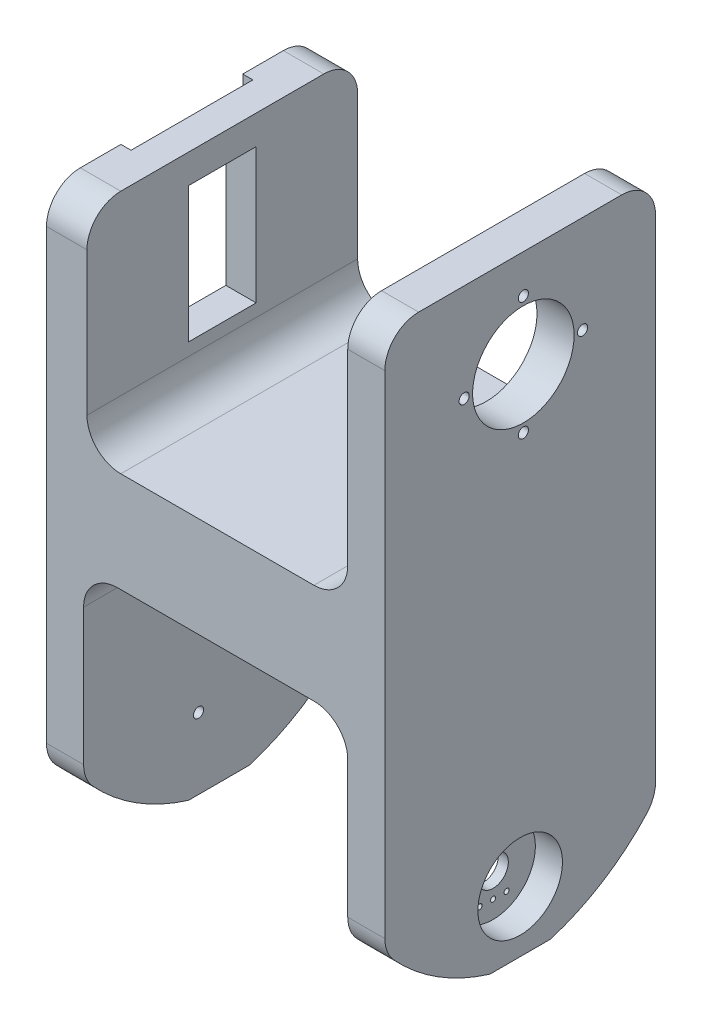
SolidWorks part; units mm, degrees
ref_plane "Front Plane" through (0, 0, 0) normal (0, 0, 1) x (1, 0, 0)
ref_plane "Top Plane" through (0, 0, 0) normal (0, 1, 0) x (1, 0, 0)
ref_plane "Right Plane" through (0, 0, 0) normal (1, 0, 0) x (0, 0, -1)
sketch "Sketch1" plane through (0, 0, 0) normal (1, 0, 0) x (0, 0, -1)
  line L1 (-40, 90) -> (40, 90)
  line L2 (-40, 90) -> (-40, -90)
  line L3 (-40, -90) -> (40, -90)
  line L4 (40, 90) -> (40, -90)
  line L5 (-40, 90) -> (40, -90) construction
  line L6 (-40, -90) -> (40, 90) construction
  point P0 (0, 0)
  dimension "D1" = 180
  dimension "D2" = 80
extrude "Boss-Extrude1" add sketch "Sketch1" along normal blind 100
sketch "Sketch2" plane through (0, 0, 40) normal (0, 0, 1) x (1, 0, 0)
  line L0 (100, -90) -> (0, -90) construction
  line L1 (10.9632, -90) -> (89.0368, -90)
  line L2 (10.9632, -90) -> (10.9632, -15.049)
  line L3 (10.9632, -15.049) -> (89.0368, -15.049)
  line L4 (89.0368, -90) -> (89.0368, -15.049)
  line L5 (10.9632, -90) -> (89.0368, -15.049) construction
  line L6 (10.9632, -15.049) -> (89.0368, -90) construction
  point P0 (50, -52.5245)
  point P6 (50, -90)
extrude "Cut-Extrude1" cut sketch "Sketch2" against normal blind 90
sketch "Sketch3" plane through (100, 0, 0) normal (1, 0, 0) x (0, 0, -1)
  line L0 (-40, -90) -> (40, -90) construction
  circle A0 centre (0, -72) radius 12.5
  dimension "D1" = 25
  dimension "D2" = 18
extrude "Cut-Extrude2" cut sketch "Sketch3" against normal blind 8
sketch "Sketch4" plane through (89.0368, 0, 0) normal (-1, 0, 0) x (0, 0, 1)
  line L0 (40, -90) -> (-40, -90) construction
  line L1 (-8.399, -72) -> (14.6736, -72) construction
  circle A0 centre (0, -72) radius 12.5
  circle A1 centre (0, -72) radius 4.5
  circle A2 centre (0, -64.75) radius 0.75
  circle A3 centre (4, -64.75) radius 0.75
  circle A4 centre (-4, -64.75) radius 0.75
  circle A5 centre (4, -79.25) radius 0.75
  circle A6 centre (0, -79.25) radius 0.75
  circle A7 centre (-4, -79.25) radius 0.75
  dimension "D1" = 25
  dimension "D3" = 9
  dimension "D4" = 1.5
  dimension "D5" = 7.25
  dimension "D2" = 18
  dimension "D6" = 4
  dimension "D7" = 4
extrude "Cut-Extrude3" cut sketch "Sketch4" against normal blind 8 contours A1 L1 | L1 A1 | A4 | A2 | A3 | A5 | A6 | A7
sketch "Sketch5" plane through (0, 0, 0) normal (-1, 0, 0) x (0, 0, 1)
  line L0 (40, -90) -> (-40, -90) construction
  line L1 (40, 90) -> (40, -90) construction
  circle A0 centre (6.03, -69) radius 11.924
  circle A1 centre (6.03, -69) radius 1.5
  dimension "D2" = 3
  dimension "D1" = 21
  dimension "D3" = 33.97
extrude "Cut-Extrude4" cut sketch "Sketch5" against normal blind 18 contours A1
sketch "Sketch6" plane through (100, 0, 0) normal (1, 0, 0) x (0, 0, -1)
  line L0 (-40, -90) -> (40, -90) construction
  line L1 (40, -90) -> (40, 90) construction
  line L2 (0, 0) -> (0, -85.7297) construction
  line L3 (40, -69.0658) -> (40, -90)
  line L4 (40, -90) -> (8.9432, -90)
  line L5 (-40, -69.0658) -> (-40, -90)
  line L6 (-40, -90) -> (-8.9432, -90)
  arc A0 (8.9432, -90) -> (40, -69.0658) centre (-9.5876, -29.0046) ccw
  arc A1 (-8.9432, -90) -> (-40, -69.0658) centre (9.5876, -29.0046) cw
extrude "Cut-Extrude5" cut sketch "Sketch6" against normal blind 110
sketch "Sketch8" plane through (0, 0, 40) normal (0, 0, 1) x (1, 0, 0)
  line L1 (100, 90) -> (0, 90) construction
  line L2 (10.9632, 165.4044) -> (89.0368, 165.4044)
  line L3 (10.9632, 165.4044) -> (10.9632, 14.5956)
  line L4 (10.9632, 14.5956) -> (89.0368, 14.5956)
  line L5 (89.0368, 165.4044) -> (89.0368, 14.5956)
  line L6 (10.9632, 165.4044) -> (89.0368, 14.5956) construction
  line L7 (10.9632, 14.5956) -> (89.0368, 165.4044) construction
  point P0 (50, 90)
extrude "Cut-Extrude7" cut sketch "Sketch8" against normal blind 110
sketch "Sketch12" plane through (10.9632, 0, 0) normal (1, 0, 0) x (0, 0, -1)
  line L0 (40, -69.0658) -> (40, 90) construction
  line L1 (-40, 90) -> (40, 90)
  line L2 (-40, 90) -> (-40, 14.5956)
  line L3 (-40, 14.5956) -> (40, 14.5956)
  line L4 (40, 90) -> (40, 14.5956)
  line L5 (40, 14.5956) -> (-40, 14.5956) construction
extrude "Boss-Extrude2" add sketch "Sketch12" along normal blind 1
sketch "Sketch13" plane through (0, 0, 0) normal (-1, 0, 0) x (0, 0, 1)
  line L1 (-10, 68.3371) -> (10, 68.3371)
  line L2 (-10, 68.3371) -> (-10, 28.3371)
  line L3 (-10, 28.3371) -> (10, 28.3371)
  line L4 (10, 68.3371) -> (10, 28.3371)
  line L5 (-10, 68.3371) -> (10, 28.3371) construction
  line L6 (-10, 28.3371) -> (10, 68.3371) construction
  point P0 (0, 48.3371)
  dimension "D1" = 20
  dimension "D2" = 40
extrude "Cut-Extrude9" cut sketch "Sketch13" against normal blind 18
sketch "Sketch14" plane through (0, 0, 0) normal (-1, 0, 0) x (0, 0, 1)
  line L1 (-18.0094, 77.9585) -> (18.0094, 77.9585)
  line L2 (-18.0094, 77.9585) -> (-18.0094, 16.2825)
  line L3 (-18.0094, 16.2825) -> (18.0094, 16.2825)
  line L4 (18.0094, 77.9585) -> (18.0094, 16.2825)
  line L5 (-18.0094, 77.9585) -> (18.0094, 16.2825) construction
  line L6 (-18.0094, 16.2825) -> (18.0094, 77.9585) construction
  point P0 (0, 47.1205)
extrude "Cut-Extrude10" cut sketch "Sketch14" against normal blind 3
sketch "Sketch15" plane through (11.9632, 0, 0) normal (1, 0, 0) x (0, 0, -1)
  line L0 (40, -69.0658) -> (40, 90) construction
  line L1 (-40, 90) -> (40, 90)
  line L2 (-40, 90) -> (-40, 76.9279)
  line L3 (-40, 76.9279) -> (40, 76.9279)
  line L4 (40, 90) -> (40, 76.9279)
extrude "Cut-Extrude11" cut sketch "Sketch15" against normal blind 30
sketch "Sketch16" plane through (100, 0, 0) normal (1, 0, 0) x (0, 0, -1)
  line L0 (40, 90) -> (-40, 90) construction
  line L1 (-40, 90) -> (-40, -69.0658) construction
  circle A0 centre (0.94, 61.16) radius 15
  dimension "D3" = 30
  dimension "D1" = 28.84
  dimension "D2" = 40.94
extrude "Cut-Extrude12" cut sketch "Sketch16" against normal blind 30
sketch "Sketch17" plane through (100, 0, 0) normal (1, 0, 0) x (0, 0, -1)
  circle A0 centre (0.94, 61.16) radius 17.5 construction
  circle A1 centre (0.94, 78.66) radius 1.5
  circle A2 centre (18.44, 61.16) radius 1.5
  circle A3 centre (0.94, 43.66) radius 1.5
  circle A4 centre (-16.56, 61.16) radius 1.5
  dimension "D1" = 35
  dimension "D2" = 3
extrude "Cut-Extrude13" cut sketch "Sketch17" against normal blind 13
fillet "Fillet1" radius 10 4 edges at (10.9632, -15.049, 0) (89.0368, -15.049, 0) (11.9632, 14.5956, 0) (89.0368, 14.5956, 0)
fillet "Fillet2" radius 10 4 edges at (5.9816, 76.9279, 40) (5.9816, 76.9279, -40) (94.5184, 90, 40) (94.5184, 90, -40)
fillet "Fillet3" radius 10 4 edges at (94.5184, -69.0658, 40) (5.4816, -69.0658, 40) (5.4816, -69.0658, -40) (94.5184, -69.0658, -40)
